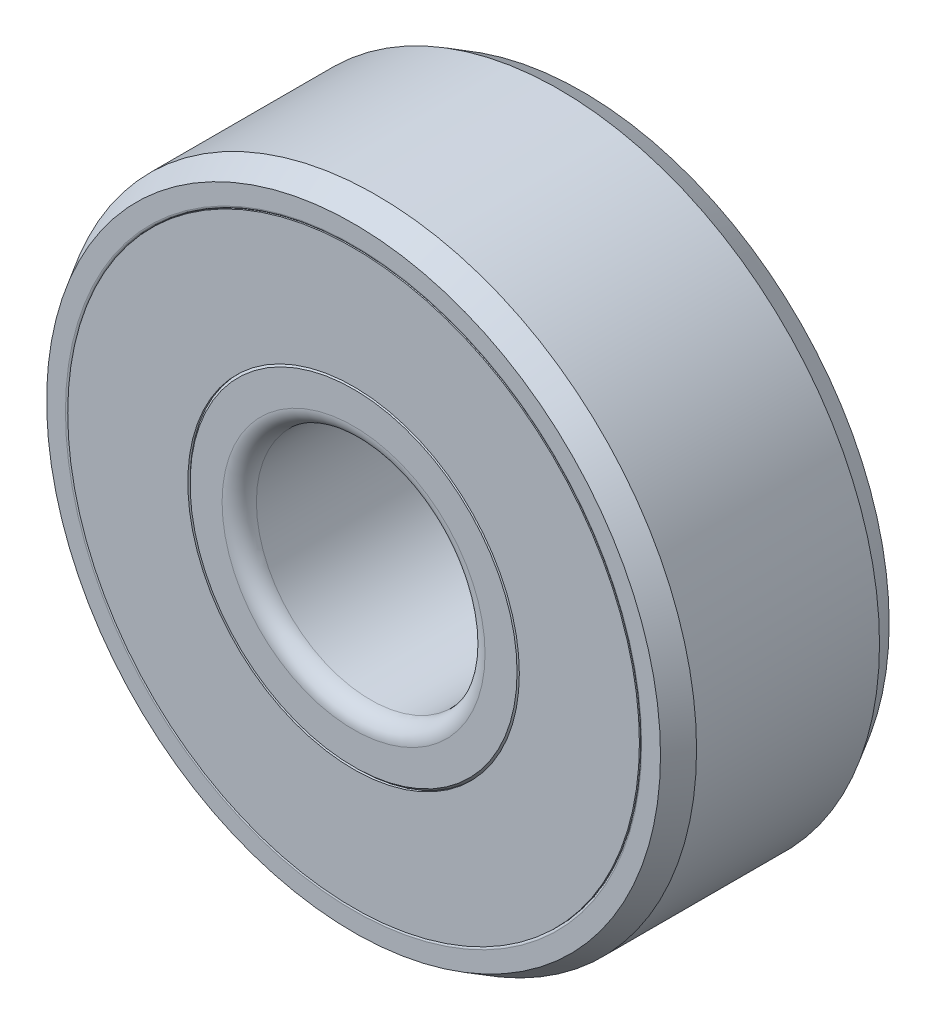
SolidWorks part; units mm, degrees
ref_plane "Front Plane" through (0, 0, 0) normal (0, 0, 1) x (1, 0, 0)
ref_plane "Top Plane" through (0, 0, 0) normal (0, 1, 0) x (1, 0, 0)
ref_plane "Right Plane" through (0, 0, 0) normal (1, 0, 0) x (0, 0, -1)
sketch "Sketch1" plane through (0, 0, 0) normal (0, 0, 1) x (1, 0, 0)
  line L0 (0, 4.75) -> (0, 7) construction
  line L1 (0, 2.5) -> (0, 4.75) construction
  line L2 (0, 7) -> (0, 6.25) construction
  line L3 (0, 6.25) -> (0, 5.5) construction
  line L4 (0, 5.5) -> (0, 4.75) construction
  circle A0 centre (0, 0) radius 2.5
  circle A1 centre (0, 0) radius 7
  circle A2 centre (0, 0) radius 6.25 construction
  circle A4 centre (0, 0) radius 3.625 construction
  point P6 (0, 3.625)
  dimension "OD" = 14
  dimension "ID" = 5
sketch "Sketch2" plane through (0, 0, 0) normal (1, 0, 0) x (0, 0, -1)
  line L0 (-2.5, 7) -> (2.5, 7) construction
  line L1 (2.5, 7) -> (2.5, -7) construction
  line L2 (2.5, 0) -> (-2.5, 0) construction
  line L3 (-2.5, 2.5) -> (-2.5, -2.5) construction
  point P2 (0, 7)
  dimension "Width" = 5
  dimension "For Shaft Diameter" = 5
  dimension "For Housing ID" = 14
sketch "Sketch3" plane through (0, 0, 0) normal (1, 0, 0) x (0, 0, -1)
  line L0 (-2, -7) -> (2, -7)
  line L3 (-2.5, -6.3) -> (-2.5, -6.7113)
  line L4 (0, -3.625) -> (0, -6.25) construction
  line L5 (-2, -7) -> (-2.5, -6.7113)
  line L6 (-2.125, -2.5) -> (2.125, -2.5)
  line L7 (-1.25, -6.25) -> (-1.25, -6.5) construction
  line L8 (-2.45, -3.625) -> (-1.25, -3.625)
  line L9 (-2.5, -3.625) -> (0, -3.625) construction
  line L11 (-2.5, -6.25) -> (-2.5, -3.625) construction
  line L12 (-2.5, -3.575) -> (-2.5, -2.875)
  line L14 (-2.5, 0) -> (2.5, 0) construction
  line L15 (-2.45, -6.25) -> (-1.25, -6.25)
  line L17 (0, 0) -> (0, -7) construction
  line L18 (-1.25, -6.5) -> (-1.25, -6.75) construction
  line L19 (2, -7) -> (2.5, -6.7113)
  line L20 (0, -6.25) -> (-2.5, -6.25) construction
  line L21 (-2.5, 2.5) -> (-2.5, -2.5) construction
  line L22 (-1.25, -6.75) -> (-1.25, -7) construction
  line L30 (-2.5, -3.575) -> (-2.45, -3.625)
  line L31 (2.45, -3.625) -> (1.25, -3.625)
  line L32 (2.5, -3.575) -> (2.45, -3.625)
  line L33 (2.5, -3.575) -> (2.5, -2.875)
  line L34 (2.45, -6.25) -> (1.25, -6.25)
  line L35 (2.5, -6.3) -> (2.5, -6.7113)
  line L36 (0, 7) -> (0, -7) construction
  arc A0 (0, -3.125) -> (0, -6.75) centre (0, -4.9375) ccw construction
  arc A1 (-1.25, -3.625) -> (1.25, -3.625) centre (0, -4.9375) cw
  arc A2 (-1.25, -6.25) -> (1.25, -6.25) centre (0, -4.9375) ccw
  arc A4 (-2.45, -6.25) -> (-2.5, -6.3) centre (-2.45, -6.3) ccw
  arc A5 (-2.125, -2.5) -> (-2.5, -2.875) centre (-2.125, -2.875) ccw
  arc A6 (2.125, -2.5) -> (2.5, -2.875) centre (2.125, -2.875) cw
  arc A7 (2.45, -6.25) -> (2.5, -6.3) centre (2.45, -6.3) cw
  point P28 (0, -4.9375)
  point P46 (-2.5, -2.5)
  point P54 (0, -2.5)
  dimension "D4" = 0.05
  dimension "D7" = 0.375
  dimension "D5" = 45
  dimension "D6" = 0.05
  dimension "D3" = 0.5
  dimension "D2" = 60
revolve "Revolve1" add sketch "Sketch3" angle 360 about L14
sketch "Sketch4" plane through (0, 0, 0) normal (1, 0, 0) x (0, 0, -1)
  line L0 (-2.45, -6.25) -> (-1.25, -6.25) construction
  line L1 (-2.5, -3.625) -> (-1.9844, -3.625)
  line L2 (-2.5, -3.625) -> (-2.5, -6.25)
  line L3 (-2.5, -6.25) -> (-1.9844, -6.25)
  line L4 (-1.9844, -3.625) -> (-1.9844, -6.25)
  line L5 (-2.5, -3.575) -> (-2.5, -2.875) construction
  line L6 (-2.5, -4.9375) -> (-2.3281, -4.9375) construction
  line L7 (-2.3281, -4.9375) -> (-2.1562, -4.9375) construction
  line L8 (-2.1562, -4.9375) -> (-1.9844, -4.9375) construction
  line L9 (-1.9844, -4.9375) -> (-1.8125, -4.9375) construction
  line L10 (-2.5, -6.25) -> (-2.5, -3.625) construction
  line L11 (-2.45, -3.625) -> (-1.25, -3.625) construction
  arc A1 (0, -3.125) -> (0, -6.75) centre (0, -4.9375) ccw construction
revolve "Revolve2" add sketch "Sketch4" angle 360 about L14
sketch "Sketch5" plane through (0, 0, 0) normal (1, 0, 0) x (0, 0, -1)
  line L2 (0, -3.125) -> (0, -6.75)
  arc A2 (0, -6.75) -> (0, -3.125) centre (0, -4.9375) cw
revolve "Revolve3" add sketch "Sketch5" angle 360 about L17
pattern_circular "CirPattern1" count 7 over 360 about axis through (0, 0, 0) along (0, 0, 1) of bodies 138
equation "\"D4@Sketch3\"=\"Width@Sketch2\"*.01"
equation "\"D6@Sketch3\"=\"Width@Sketch2\"*.01"
equation "\"D7@Sketch3\"=\"Width@Sketch2\"*.075"
equation "\"D3@Sketch3\"=\"Width@Sketch2\"*.1"
